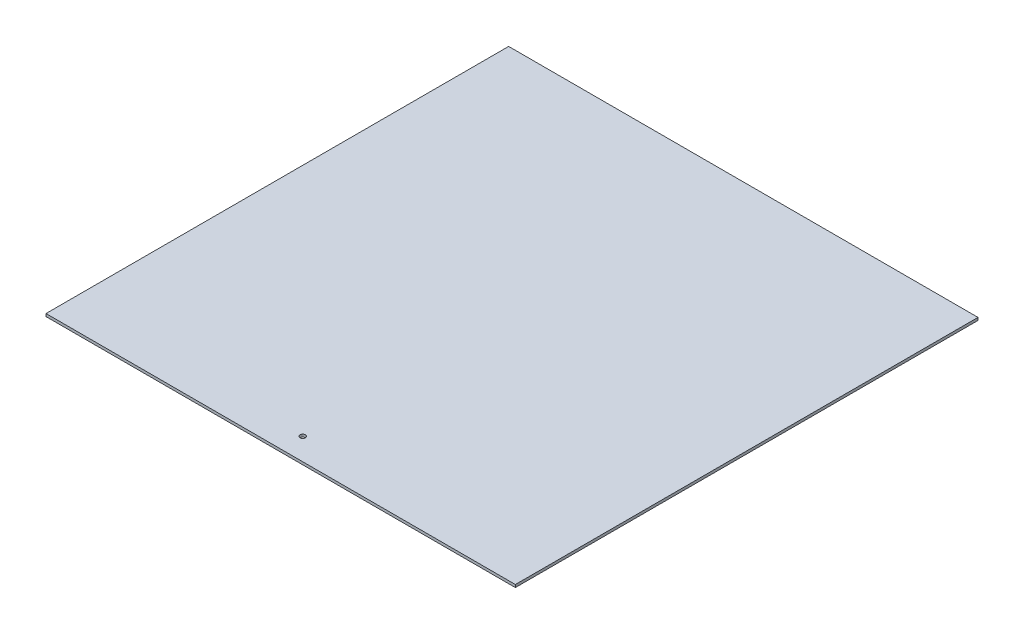
SolidWorks part; units mm, degrees
ref_plane "Front Plane" through (0, 0, 0) normal (0, 0, 1) x (1, 0, 0)
ref_plane "Top Plane" through (0, 0, 0) normal (0, 1, 0) x (1, 0, 0)
ref_plane "Right Plane" through (0, 0, 0) normal (1, 0, 0) x (0, 0, -1)
sketch "Sketch1" plane through (0, 0, 0) normal (0, 1, 0) x (1, 0, 0)
  line L0 (-175, 171.4429) -> (175, 171.4429)
  line L1 (175, -173.5571) -> (175, 171.4429)
  line L2 (-175, -173.5571) -> (175, -173.5571)
  line L3 (-175, -173.5571) -> (-175, 171.4429)
  circle A0 centre (0, -157.0922) radius 2
  point P0 (0, -3.5571)
  dimension "D1" = 175
  dimension "D2" = 170
  dimension "D3" = 175
  dimension "D4" = 175
  dimension "D5" = 350
extrude "Boss-Extrude1" add sketch "Sketch1" along normal blind 2
